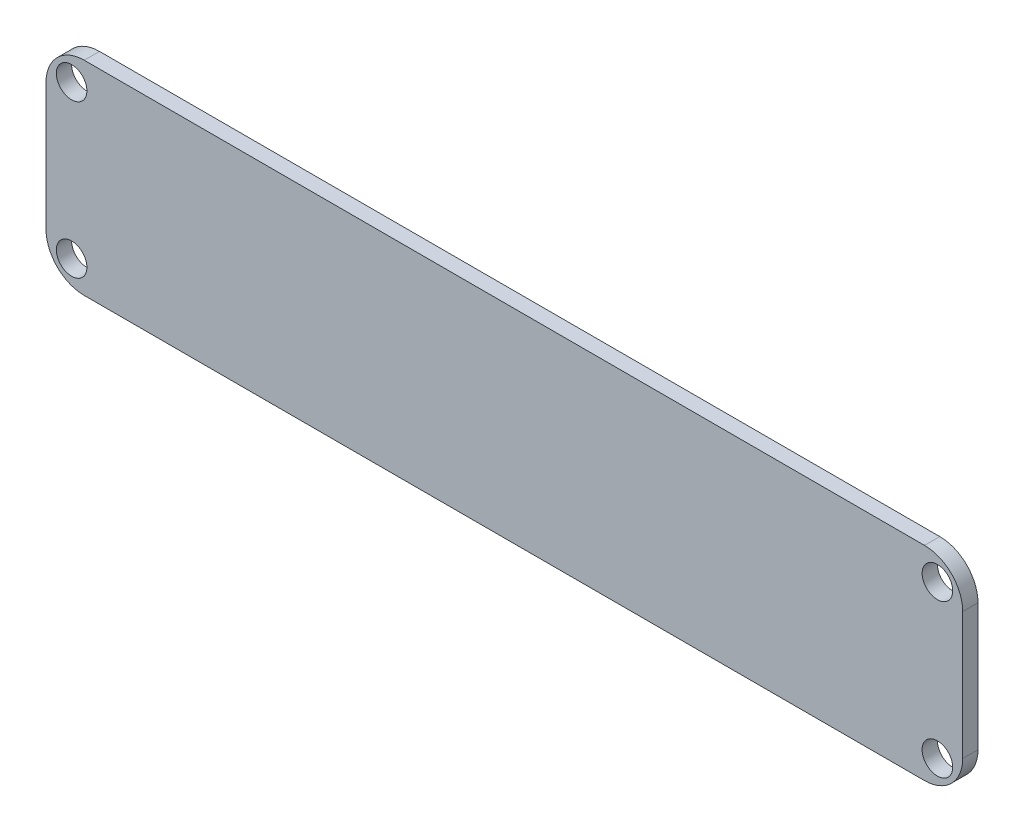
SolidWorks part; units mm, degrees
ref_plane "前视基准面" through (0, 0, 0) normal (0, 0, 1) x (1, 0, 0)
ref_plane "上视基准面" through (0, 0, 0) normal (0, 1, 0) x (1, 0, 0)
ref_plane "右视基准面" through (0, 0, 0) normal (1, 0, 0) x (0, 0, -1)
other "Configuration Table"
sketch "草图1" plane through (0, 0, 0) normal (0, 0, 1) x (1, 0, 0)
  line L1 (0, 0) -> (72, 0)
  line L2 (0, 0) -> (0, 16)
  line L3 (0, 16) -> (72, 16)
  line L4 (72, 0) -> (72, 16)
  dimension "D1" = 72
  dimension "D2" = 16
extrude "凸台-拉伸1" add sketch "草图1" along normal blind 1.2
fillet "圆角1" radius 3 4 edges at (0, 0, 0.6) (0, 16, 0.6) (72, 0, 0.6) (72, 16, 0.6)
sketch "草图3" plane through (0, 0, 0) normal (0, 0, -1) x (-1, 0, 0)
  circle A0 centre (-70.0129, 14.013) radius 1.2
  circle A1 centre (-70.0127, 2.0127) radius 1.2
  circle A2 centre (-2.0119, 14.012) radius 1.2
  circle A3 centre (-2.0125, 2.013) radius 1.2
  dimension "D1" = 2.4
extrude "切除-拉伸1" cut sketch "草图3" against normal up to next
